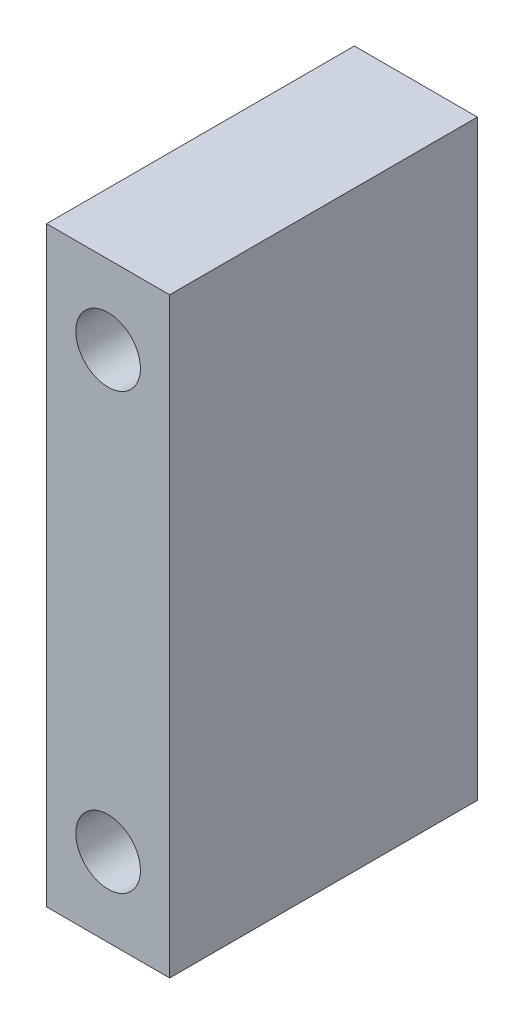
SolidWorks part; units mm, degrees
ref_plane "Plan de face" through (0, 0, 0) normal (0, 0, 1) x (1, 0, 0)
ref_plane "Plan de dessus" through (0, 0, 0) normal (0, 1, 0) x (1, 0, 0)
ref_plane "Plan de droite" through (0, 0, 0) normal (1, 0, 0) x (0, 0, -1)
sketch "Esquisse1" plane through (0, 0, 0) normal (0, 0, 1) x (1, 0, 0)
  line L0 (-4, 35.45) -> (-4, 38.45) construction
  line L1 (-8, 38.45) -> (0, 38.45)
  line L2 (-8, 38.45) -> (-8, 0)
  line L3 (-8, 0) -> (0, 0)
  line L4 (0, 38.45) -> (0, 0)
  line L5 (-4, 3) -> (-4, 0) construction
  circle A0 centre (-4, 33.35) radius 2.1
  circle A1 centre (-4, 5.1) radius 2.1
  point P9 (-4, 38.45)
  point P11 (-4, 35.45)
  dimension "D2" = 4.2
  dimension "D1" = 8
  dimension "D3" = 3
  dimension "D4" = 28.25
extrude "Boss.-Extru.1" add sketch "Esquisse1" along normal blind 20
